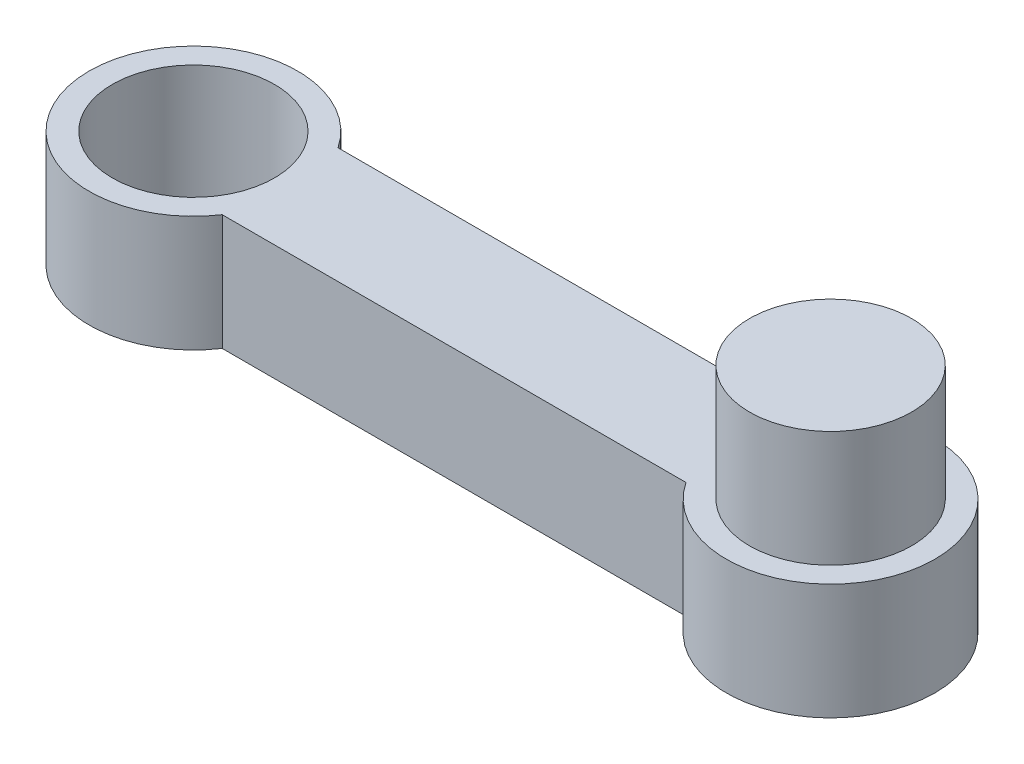
SolidWorks part; units mm, degrees
ref_plane "Front Plane" through (0, 0, 0) normal (0, 0, 1) x (1, 0, 0)
ref_plane "Top Plane" through (0, 0, 0) normal (0, 1, 0) x (1, 0, 0)
ref_plane "Right Plane" through (0, 0, 0) normal (1, 0, 0) x (0, 0, -1)
sketch "Sketch1" plane through (0, 0, 0) normal (0, 1, 0) x (1, 0, 0)
  line L0 (-242.6257, 275.7418) -> (-242.6257, 275.9924)
  line L1 (-242.6257, 175.9924) -> (157.3743, 175.9924)
  line L2 (-242.6257, 175.9924) -> (-242.6257, 176.2431)
  line L3 (-242.6257, 275.9924) -> (157.3743, 275.9924)
  line L4 (157.3743, 175.9924) -> (157.3743, 176.2431)
  line L5 (157.3743, 275.7418) -> (157.3743, 275.9924)
  arc A0 (-242.6257, 275.7418) -> (-242.6257, 176.2431) centre (-317.6257, 225.9924) ccw
  arc A1 (157.3743, 176.2431) -> (157.3743, 275.7418) centre (232.3743, 225.9924) ccw
  dimension "D3" = 180
  dimension "D6" = 180
  dimension "D1" = 400
  dimension "D2" = 100
  dimension "D4" = 50
  dimension "D5" = 75
  dimension "D7" = 75
  dimension "D8" = 50
extrude "Boss-Extrude1" add sketch "Sketch1" along normal blind 100
sketch "Sketch2" plane through (0, 100, 0) normal (0, 1, 0) x (1, 0, 0)
  circle A0 centre (-317.6257, 225.9924) radius 70
  dimension "D1" = 140
extrude "Cut-Extrude1" cut sketch "Sketch2" against normal blind 100
sketch "Sketch3" plane through (0, 100, 0) normal (0, 1, 0) x (1, 0, 0)
  circle A0 centre (232.3743, 225.9924) radius 70
  dimension "D1" = 140
extrude "Boss-Extrude2" add sketch "Sketch3" along normal blind 100
sketch "Sketch4" plane through (0, 100, 0) normal (0, 1, 0) x (1, 0, 0)
  line L0 (-317.6257, 295.9924) -> (-317.6257, 155.9924) construction
  line L1 (-387.6257, 225.9924) -> (-247.6257, 225.9924) construction
  circle A0 centre (-317.6257, 225.9924) radius 70 construction
  point P7 (-317.6257, 225.9924)
  point P8 (232.3743, 225.9924)
